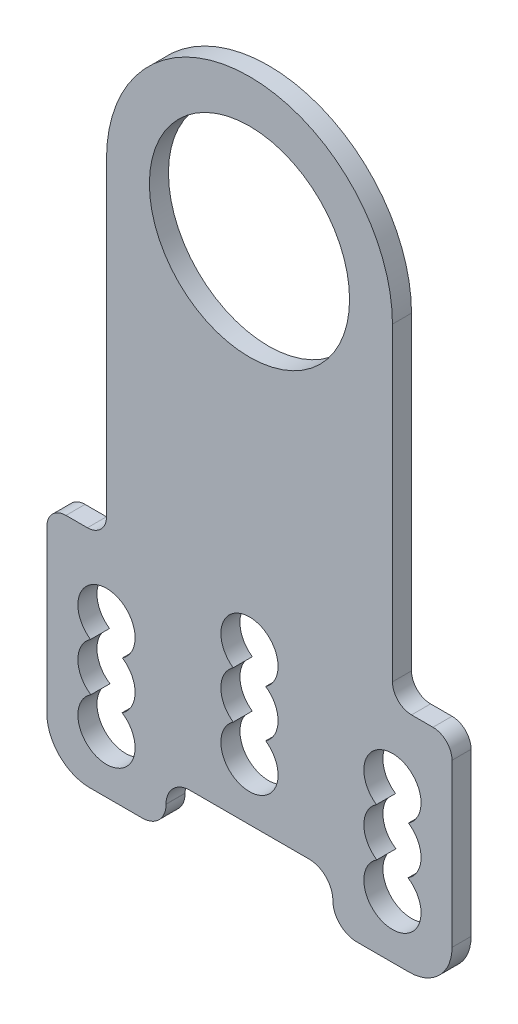
SolidWorks part; units mm, degrees
ref_plane "前视基准面" through (0, 0, 0) normal (0, 0, 1) x (1, 0, 0)
ref_plane "上视基准面" through (0, 0, 0) normal (0, 1, 0) x (1, 0, 0)
ref_plane "右视基准面" through (0, 0, 0) normal (1, 0, 0) x (0, 0, -1)
sketch "草图1" plane through (0, 0, 0) normal (0, 0, 1) x (1, 0, 0)
  line L0 (-15, 0) -> (-15, -32.5)
  line L1 (-17, -34.5) -> (-19.25, -34.5)
  line L2 (15, 0) -> (15, -32.5)
  line L3 (6.25, -52.9741) -> (-6.25, -52.9741)
  line L4 (16.75, -58) -> (11.25, -58)
  line L5 (21.25, -36.5) -> (21.25, -53.5)
  line L6 (17, -34.5) -> (19.25, -34.5)
  line L7 (-21.25, -36.5) -> (-21.25, -53.5)
  line L9 (-16.75, -58) -> (-11.25, -58)
  line L15 (-8.75, -55.4741) -> (-8.75, -55.5)
  line L16 (8.75, -55.4741) -> (8.75, -55.5)
  arc A0 (15, 0) -> (-15, 0) centre (0, 0) ccw
  arc A1 (-17, -34.5) -> (-15, -32.5) centre (-17, -32.5) ccw
  arc A2 (17, -34.5) -> (15, -32.5) centre (17, -32.5) cw
  arc A3 (-16.6386, -49.4871) -> (-13.3614, -49.4871) centre (-15, -52) ccw
  arc A4 (-16.6777, -44.4871) -> (-16.6386, -49.4871) centre (-15, -46.9741) ccw
  arc A5 (-13.3614, -49.4871) -> (-13.3223, -44.4871) centre (-15, -46.9741) ccw
  arc A6 (21.25, -36.5) -> (19.25, -34.5) centre (19.25, -36.5) ccw
  arc A7 (-19.25, -34.5) -> (-21.25, -36.5) centre (-19.25, -36.5) ccw
  circle A8 centre (0, 0) radius 10.5
  arc A9 (-1.7048, -39.5685) -> (-1.7048, -44.5056) centre (0, -42.0371) ccw
  arc A10 (-1.7048, -44.5056) -> (1.7048, -44.5056) centre (0, -46.9741) ccw
  arc A11 (-13.3223, -44.4871) -> (-16.6777, -44.4871) centre (-15, -42) ccw
  arc A14 (1.7048, -39.5685) -> (-1.7048, -39.5685) centre (0, -37.1) ccw
  arc A15 (1.7048, -44.5056) -> (1.7048, -39.5685) centre (0, -42.0371) ccw
  arc A20 (13.3614, -49.4871) -> (16.6386, -49.4871) centre (15, -52) ccw
  arc A21 (16.6386, -49.4871) -> (16.6777, -44.4871) centre (15, -46.9741) ccw
  arc A22 (16.6777, -44.4871) -> (13.3223, -44.4871) centre (15, -42) ccw
  arc A23 (13.3223, -44.4871) -> (13.3614, -49.4871) centre (15, -46.9741) ccw
  arc A29 (-11.25, -58) -> (-8.75, -55.5) centre (-11.25, -55.5) ccw
  arc A30 (-6.25, -52.9741) -> (-8.75, -55.4741) centre (-6.25, -55.4741) ccw
  arc A31 (8.75, -55.4741) -> (6.25, -52.9741) centre (6.25, -55.4741) ccw
  arc A32 (8.75, -55.5) -> (11.25, -58) centre (11.25, -55.5) ccw
  arc A33 (16.75, -58) -> (21.25, -53.5) centre (16.75, -53.5) ccw
  arc A43 (-21.25, -53.5) -> (-16.75, -58) centre (-16.75, -53.5) ccw
  dimension "D1" = 2
  dimension "D2" = 21
extrude "凸台-拉伸1" add sketch "草图1" along normal blind 2
